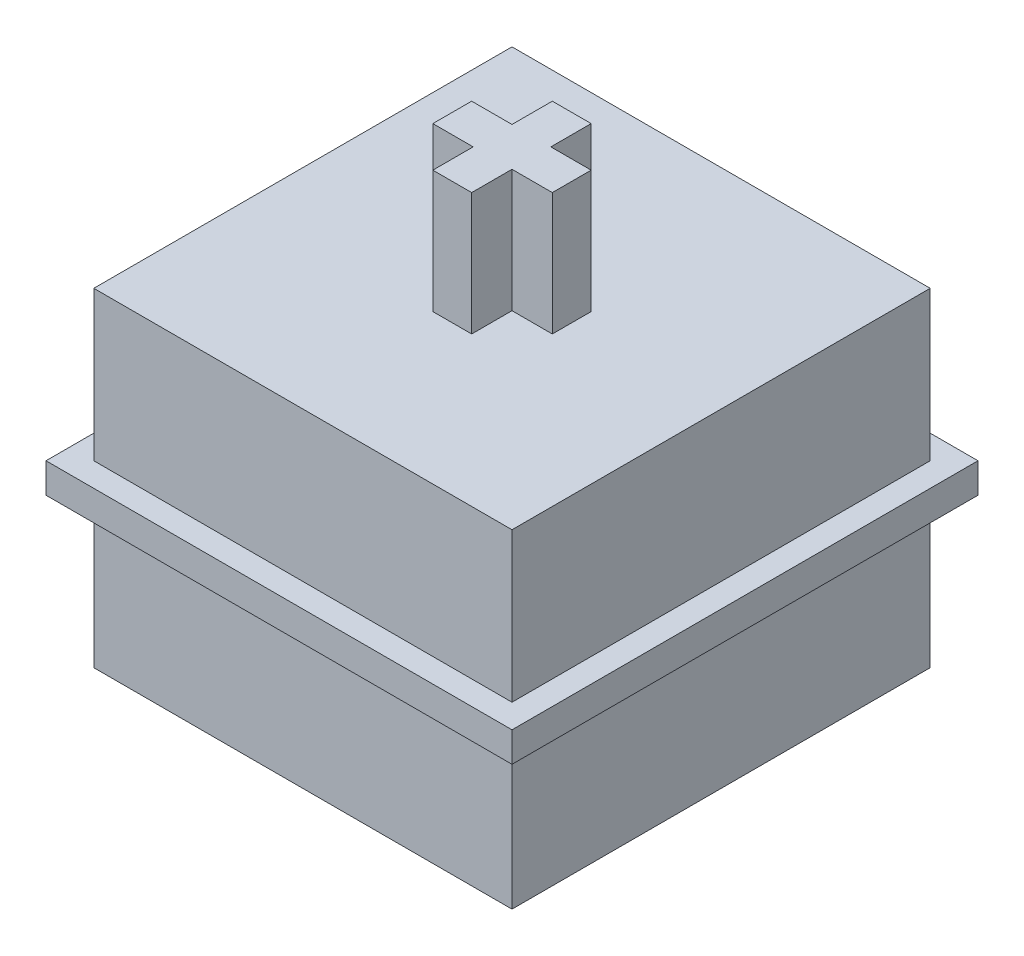
SolidWorks part; units mm, degrees
ref_plane "前视基准面" through (0, 0, 0) normal (0, 0, 1) x (1, 0, 0)
ref_plane "上视基准面" through (0, 0, 0) normal (0, 1, 0) x (1, 0, 0)
ref_plane "右视基准面" through (0, 0, 0) normal (1, 0, 0) x (0, 0, -1)
sketch "草图1" plane through (0, 0, 0) normal (0, 1, 0) x (1, 0, 0)
  line L1 (4.1074, -4.9752) -> (-9.8926, -4.9752)
  line L2 (4.1074, -4.9752) -> (4.1074, 9.0248)
  line L3 (4.1074, 9.0248) -> (-9.8926, 9.0248)
  line L4 (-9.8926, -4.9752) -> (-9.8926, 9.0248)
  dimension "D1" = 14
  dimension "D2" = 14
extrude "凸台-拉伸1" add sketch "草图1" along normal blind 5
sketch "草图2" plane through (0, 0, 0) normal (0, -1, 0) x (1, 0, 0)
  line L0 (4.1074, -9.0248) -> (-9.8926, -9.0248) construction
  line L1 (4.1074, 4.9752) -> (4.1074, -9.0248) construction
  circle A0 centre (-2.8926, -2.0248) radius 1.925
  dimension "D1" = 3.85
  dimension "D2" = 7
  dimension "D3" = 7
extrude "凸台-拉伸2" add sketch "草图2" along normal blind 2.8
chamfer "倒角1" distance 0.5 angle 45 1 edges at (-2.8926, -2.8, -3.9498)
sketch "草图3" plane through (0, 5, 0) normal (0, 1, 0) x (1, 0, 0)
  line L0 (-9.8926, 9.0248) -> (-9.8926, -4.9752) construction
  line L1 (-10.6926, 9.8248) -> (4.9074, 9.8248)
  line L2 (-10.6926, 9.8248) -> (-10.6926, -5.7752)
  line L3 (-10.6926, -5.7752) -> (4.9074, -5.7752)
  line L4 (4.9074, 9.8248) -> (4.9074, -5.7752)
  line L5 (4.1074, 9.0248) -> (-9.8926, 9.0248) construction
  dimension "D1" = 15.6
  dimension "D2" = 15.6
  dimension "D3" = 0.8
  dimension "D4" = 0.8
extrude "凸台-拉伸3" add sketch "草图3" along normal blind 1
sketch "草图4" plane through (0, 6, 0) normal (0, 1, 0) x (1, 0, 0)
  line L1 (-9.8926, 9.0248) -> (4.1074, 9.0248)
  line L2 (-9.8926, 9.0248) -> (-9.8926, -4.9752)
  line L3 (-9.8926, -4.9752) -> (4.1074, -4.9752)
  line L4 (4.1074, 9.0248) -> (4.1074, -4.9752)
extrude "凸台-拉伸4" add sketch "草图4" along normal blind 5
sketch "草图5" plane through (0, 11, 0) normal (0, 1, 0) x (1, 0, 0)
  line L0 (-3.5426, 2.6748) -> (-3.5426, 4.0248)
  line L1 (-3.5426, 4.0248) -> (-2.2426, 4.0248)
  line L2 (-2.2426, 4.0248) -> (-2.2426, 2.6748)
  line L3 (-2.2426, 2.6748) -> (-0.8926, 2.6748)
  line L4 (-0.8926, 2.6748) -> (-0.8926, 1.3748)
  line L5 (-0.8926, 1.3748) -> (-2.2426, 1.3748)
  line L6 (-2.2426, 1.3748) -> (-2.2426, 0.0248)
  line L7 (-2.2426, 0.0248) -> (-3.5426, 0.0248)
  line L8 (-3.5426, 0.0248) -> (-3.5426, 1.3748)
  line L9 (-3.5426, 1.3748) -> (-4.8926, 1.3748)
  line L10 (-4.8926, 1.3748) -> (-4.8926, 2.6748)
  line L11 (-4.8926, 2.6748) -> (-3.5426, 2.6748)
  line L12 (4.9074, 9.8248) -> (-10.6926, 9.8248) construction
  line L13 (4.9074, -5.7752) -> (4.9074, 9.8248) construction
  point P16 (-16.5325, 0.9456)
  dimension "D1" = 1.3
  dimension "D2" = 1.3
  dimension "D3" = 1.3
  dimension "D4" = 1.3
  dimension "D5" = 4
  dimension "D6" = 4
  dimension "D7" = 5.8
  dimension "D8" = 5.8
extrude "凸台-拉伸5" add sketch "草图5" along normal blind 4.1
